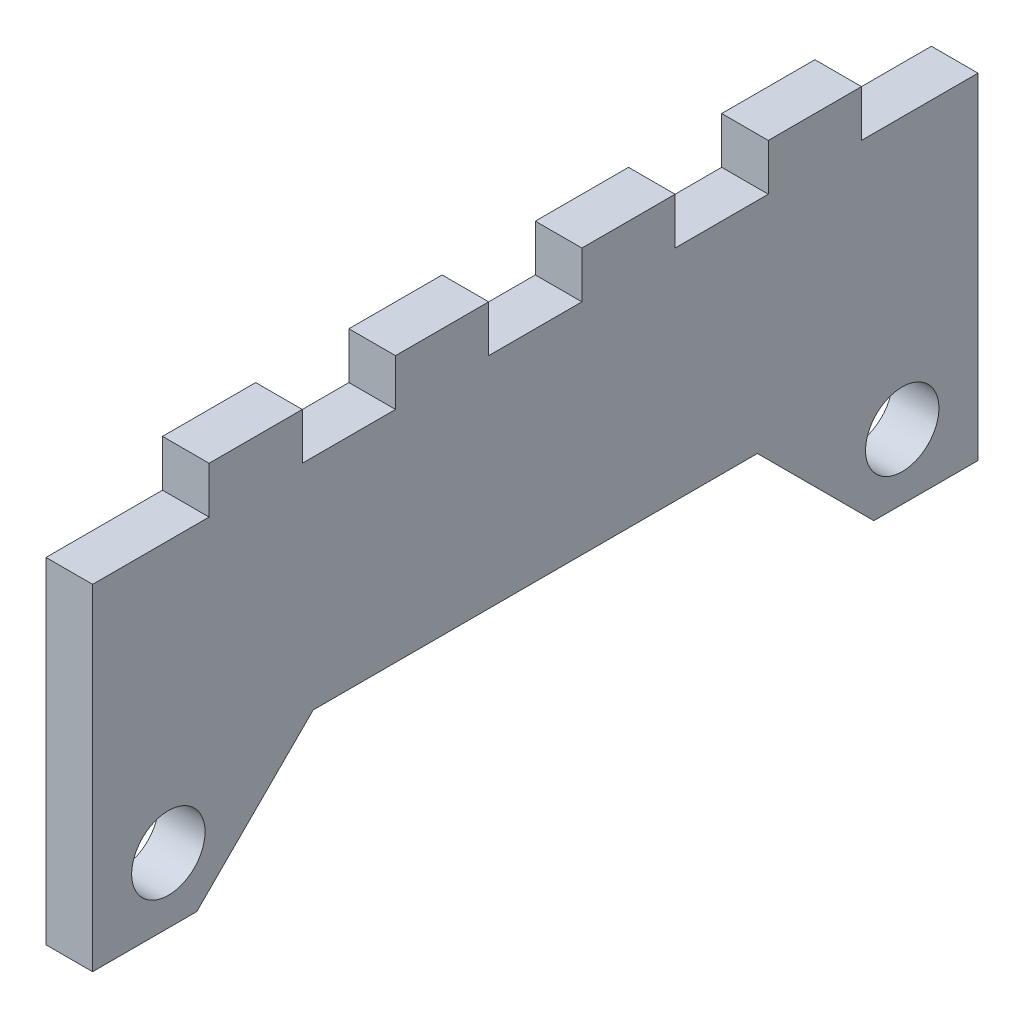
SolidWorks part; units mm, degrees
material "Acrylic (Medium-high impact)"
ref_plane "Front Plane" through (0, 0, 0) normal (0, 0, 1) x (1, 0, 0)
ref_plane "Top Plane" through (0, 0, 0) normal (0, 1, 0) x (1, 0, 0)
ref_plane "Right Plane" through (0, 0, 0) normal (1, 0, 0) x (0, 0, -1)
sketch "Sketch1" plane through (0, 0, 0) normal (1, 0, 0) x (0, 0, -1)
  line L0 (30.1625, 11.43) -> (30.1625, 0) construction
  line L1 (0, 0) -> (7.0965, 0)
  line L2 (0, 0) -> (0, 22.86)
  line L3 (0, 22.86) -> (7.9375, 22.86)
  line L4 (60.325, 0) -> (60.325, 22.86)
  line L5 (26.9875, 22.86) -> (26.9875, 26.035)
  line L6 (26.9875, 26.035) -> (20.6375, 26.035)
  line L7 (20.6375, 26.035) -> (20.6375, 22.86)
  line L8 (33.3375, 26.035) -> (33.3375, 22.86)
  line L9 (39.6875, 26.035) -> (33.3375, 26.035)
  line L10 (39.6875, 22.86) -> (39.6875, 26.035)
  line L11 (46.0375, 26.035) -> (46.0375, 22.86)
  line L12 (52.3875, 26.035) -> (46.0375, 26.035)
  line L13 (52.3875, 22.86) -> (52.3875, 26.035)
  line L14 (14.2875, 22.86) -> (14.2875, 26.035)
  line L15 (14.2875, 26.035) -> (7.9375, 26.035)
  line L16 (7.9375, 26.035) -> (7.9375, 22.86)
  line L17 (14.2875, 22.86) -> (20.6375, 22.86)
  line L18 (26.9875, 22.86) -> (33.3375, 22.86)
  line L19 (39.6875, 22.86) -> (46.0375, 22.86)
  line L20 (52.3875, 22.86) -> (60.325, 22.86)
  line L21 (7.0965, 0) -> (15.0265, 7.93)
  line L22 (15.0265, 7.93) -> (45.2985, 7.93)
  line L23 (53.2285, 0) -> (45.2985, 7.93)
  line L24 (53.2285, 0) -> (60.325, 0)
  circle A0 centre (5.1625, 4.43) radius 2.5
  circle A1 centre (55.1625, 4.43) radius 2.5
  point P31 (30.1625, 7.93)
  dimension "D11" = 5
  dimension "D1" = 22.86
  dimension "D2" = 60.325
  dimension "D3" = 3.175
  dimension "D4" = 6.35
  dimension "D5" = 3.175
  dimension "D8" = 6.35
  dimension "D9" = 6.35
  dimension "D10" = 7.9375
  dimension "D12" = 4.43
  dimension "D13" = 50
  dimension "D14" = 3.5
  dimension "D15" = 45
  dimension "D16" = 4.5
  dimension "D6" = 3
  dimension "D7" = 2
extrude "Boss-Extrude1" add sketch "Sketch1" along normal blind 3.175
